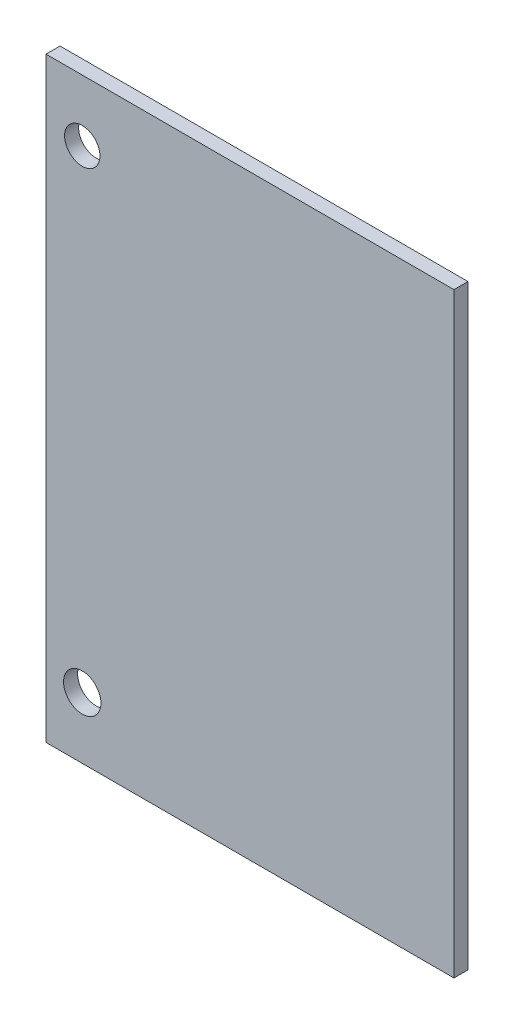
SolidWorks part; units mm, degrees
ref_plane "Спереди" through (0, 0, 0) normal (0, 0, 1) x (1, 0, 0)
ref_plane "Сверху" through (0, 0, 0) normal (0, 1, 0) x (1, 0, 0)
ref_plane "Справа" through (0, 0, 0) normal (1, 0, 0) x (0, 0, -1)
sketch "Эскиз1" plane through (0, 0, 0) normal (0, 0, 1) x (1, 0, 0)
  line L0 (-336.9233, 30.5326) -> (-273.3233, -9.9674) construction
  line L1 (-340.0233, 35.7826) -> (-270.2233, 35.7826)
  line L2 (-340.0233, 35.7826) -> (-340.0233, -15.2174)
  line L3 (-340.0233, -15.2174) -> (-270.2233, -15.2174)
  line L4 (-270.2233, 35.7826) -> (-270.2233, -15.2174)
  line L5 (-273.3233, 30.5326) -> (-336.9233, -9.9674) construction
  circle A0 centre (-336.9233, 30.5326) radius 1.5121
  circle A1 centre (-336.9233, -9.9674) radius 1.6
  circle A2 centre (-273.3233, 30.5326) radius 1.6
  circle A3 centre (-273.3233, -9.9674) radius 1.6
  point P6 (-305.1233, 35.7826)
  point P9 (-305.1233, 10.2826)
  point P12 (-270.2233, 10.2826)
  dimension "D3" = 63.6
  dimension "D1" = 51
  dimension "D2" = 69.8
  dimension "D4" = 40.5
extrude "Бобышка-Вытянуть1" add sketch "Эскиз1" along normal blind 1.2
sketch "Эскиз2" plane through (0, 0, 1.2) normal (0, 0, 1) x (1, 0, 0)
  line L0 (-270.2233, 35.7826) -> (-340.0233, 35.7826) construction
  line L1 (-305.1233, 35.7826) -> (-270.2233, 35.7826)
  line L2 (-305.1233, 35.7826) -> (-305.1233, -15.2174)
  line L3 (-305.1233, -15.2174) -> (-270.2233, -15.2174)
  line L4 (-270.2233, 35.7826) -> (-270.2233, -15.2174)
extrude "Вырез-Вытянуть1" cut sketch "Эскиз2" against normal through all
